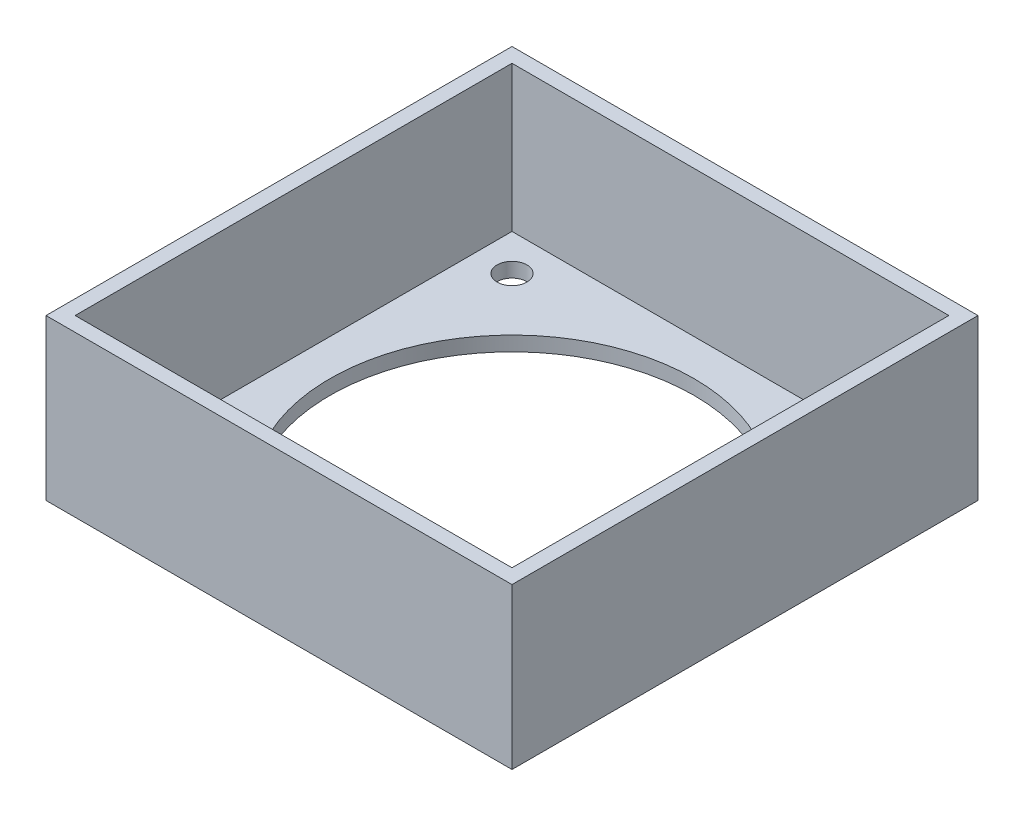
SolidWorks part; units mm, degrees
ref_plane "前视基准面" through (0, 0, 0) normal (0, 0, 1) x (1, 0, 0)
ref_plane "上视基准面" through (0, 0, 0) normal (0, 1, 0) x (1, 0, 0)
ref_plane "右视基准面" through (0, 0, 0) normal (1, 0, 0) x (0, 0, -1)
sketch "草图1" plane through (0, 0, 0) normal (0, 1, 0) x (1, 0, 0)
  line L1 (-34.8747, 22.0142) -> (29.1253, 22.0142)
  line L2 (-34.8747, 22.0142) -> (-34.8747, -41.9858)
  line L3 (-34.8747, -41.9858) -> (29.1253, -41.9858)
  line L4 (29.1253, 22.0142) -> (29.1253, -41.9858)
  dimension "D1" = 64
  dimension "D2" = 64
extrude "凸台-拉伸1" add sketch "草图1" along normal blind 22
shell "抽壳1" thickness 2
sketch "草图2" plane through (0, 2, 0) normal (0, 1, 0) x (1, 0, 0)
  line L0 (27.1253, 20.0142) -> (-32.8747, 20.0142) construction
  line L1 (-32.8747, 20.0142) -> (-32.8747, -39.9858) construction
  circle A0 centre (-2.8747, -9.9858) radius 25
  point P0 (-2.8747, 20.0142)
  point P1 (-32.8747, -9.9858)
  point P4 (-2.8747, -9.9858)
extrude "切除-拉伸1" cut sketch "草图2" against normal blind 22
sketch "草图3" plane through (0, 2, 0) normal (0, 1, 0) x (1, 0, 0)
  line L0 (27.1253, 20.0142) -> (-32.8747, 20.0142) construction
  line L1 (-27.8747, 15.0142) -> (22.1253, 15.0142) construction
  line L2 (-27.8747, 15.0142) -> (-27.8747, -34.9858) construction
  line L3 (-27.8747, -34.9858) -> (22.1253, -34.9858) construction
  line L4 (22.1253, 15.0142) -> (22.1253, -34.9858) construction
  line L5 (-32.8747, 20.0142) -> (-32.8747, -39.9858) construction
  circle A0 centre (-27.8747, 15.0142) radius 2.05
  circle A1 centre (22.1253, 15.0142) radius 2.05
  circle A2 centre (-27.8747, -34.9858) radius 2.05
  circle A3 centre (22.1253, -34.9858) radius 2.05
  point P4 (-2.8747, 20.0142)
  point P5 (-2.8747, 15.0142)
  point P8 (-27.8747, -9.9858)
  point P9 (-32.8747, -9.9858)
  dimension "D1" = 50
  dimension "D2" = 50
extrude "切除-拉伸2" cut sketch "草图3" against normal blind 22
